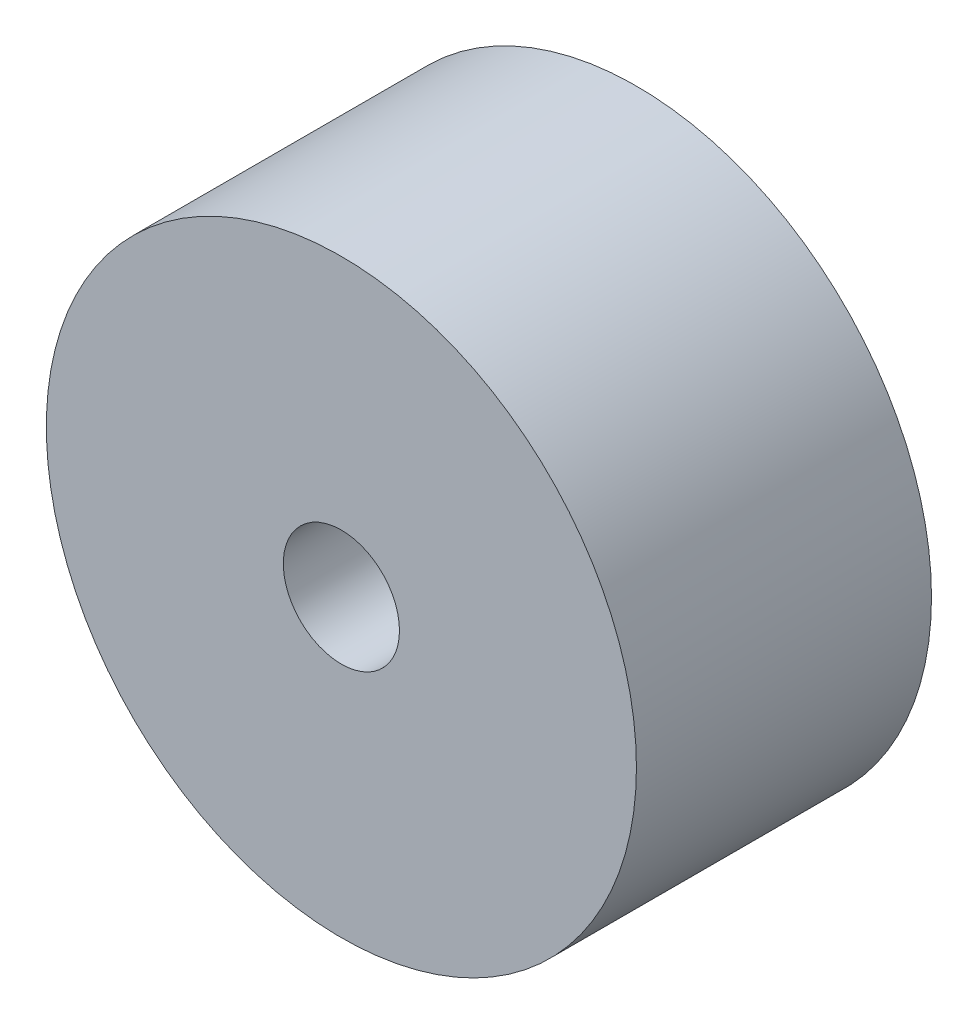
SolidWorks part; units mm, degrees
ref_plane "Front Plane" through (0, 0, 0) normal (0, 0, 1) x (1, 0, 0)
ref_plane "Top Plane" through (0, 0, 0) normal (0, 1, 0) x (1, 0, 0)
ref_plane "Right Plane" through (0, 0, 0) normal (1, 0, 0) x (0, 0, -1)
sketch "Sketch1" plane through (0, 0, 0) normal (0, 0, 1) x (1, 0, 0)
  circle A0 centre (0, 0) radius 12.7
  dimension "D1" = 25.4
extrude "Boss-Extrude1" add sketch "Sketch1" along normal blind 12.7
sketch "Sketch2" plane through (0, 0, 12.7) normal (0, 0, 1) x (1, 0, 0)
  circle A0 centre (0, 0) radius 2.5
  dimension "D1" = 5
extrude "Cut-Extrude1" cut sketch "Sketch2" against normal blind 16
